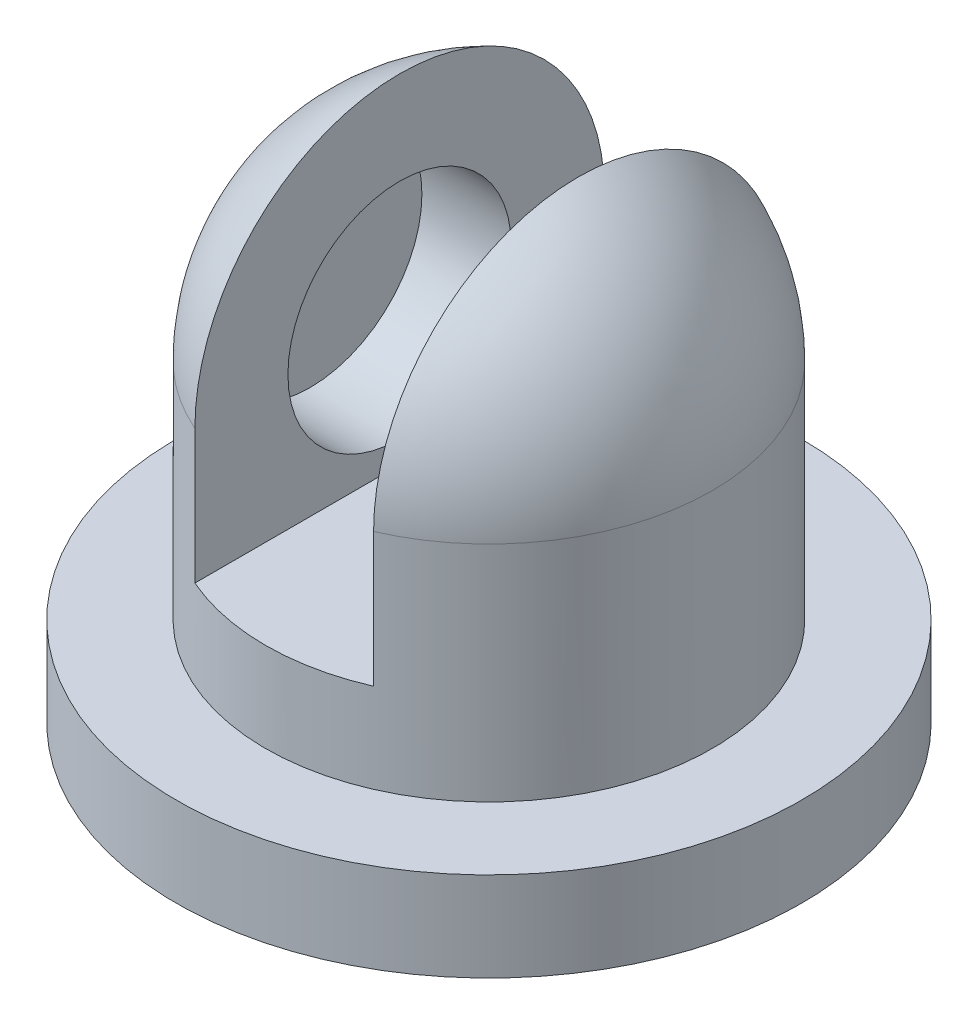
SolidWorks part; units mm, degrees
ref_plane "Front Plane" through (0, 0, 0) normal (0, 0, 1) x (1, 0, 0)
ref_plane "Top Plane" through (0, 0, 0) normal (0, 1, 0) x (1, 0, 0)
ref_plane "Right Plane" through (0, 0, 0) normal (1, 0, 0) x (0, 0, -1)
sketch "Sketch1" plane through (0, 0, 0) normal (0, 1, 0) x (1, 0, 0)
  line L0 (-5, 0) -> (5, 0)
  arc A0 (-5, 0) -> (5, 0) centre (0, 0) cw
  dimension "D1" = 5
revolve "Revolve1" add sketch "Sketch1" angle 180 about L0
sketch "Sketch2" plane through (0, 0, 0) normal (0, -1, 0) x (1, 0, 0)
  circle A0 centre (0, 0) radius 5
extrude "Boss-Extrude1" add sketch "Sketch2" along normal blind 5
sketch "Sketch3" plane through (0, -5, 0) normal (0, -1, 0) x (1, 0, 0)
  circle A0 centre (0, 0) radius 7
  dimension "D1" = 14
extrude "Boss-Extrude2" add sketch "Sketch3" along normal blind 2
sketch "Sketch4" plane through (0, 0, 0) normal (0, 1, 0) x (1, 0, 0)
  line L1 (0, 5) -> (2, 5)
  line L2 (0, 5) -> (0, -5)
  line L3 (0, -5) -> (2, -5)
  line L4 (2, 5) -> (2, -5)
  circle A0 centre (0, 0) radius 5 construction
  circle A1 centre (0, 0) radius 5 construction
  dimension "D1" = 2
extrude "Cut-Extrude1" cut sketch "Sketch4" along normal through all and the other way blind 3
sketch "Sketch6" plane through (2, 0, 0) normal (-1, 0, 0) x (0, 0, 1)
  circle A0 centre (0, 0) radius 2.5
  dimension "D1" = 5
extrude "Cut-Extrude2" cut sketch "Sketch6" against normal blind 2
mirror "Mirror1" about plane through (0, 0, 0) normal (1, 0, 0) of "Cut-Extrude1", "Cut-Extrude2"
